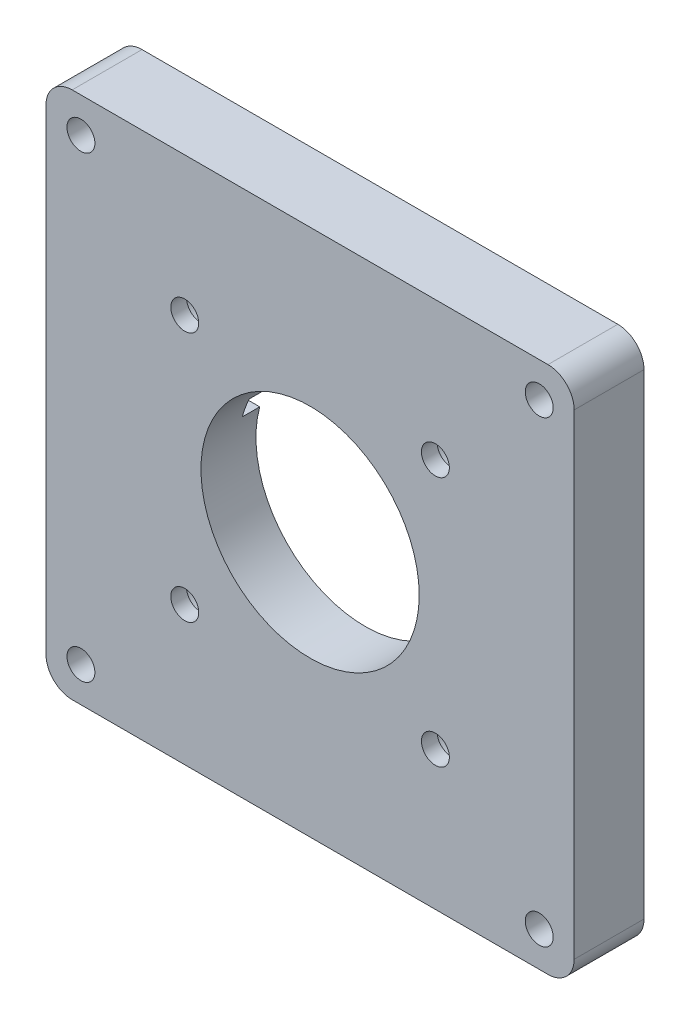
SolidWorks part; units mm, degrees
material "ABS"
ref_plane "Front Plane" through (0, 0, 0) normal (0, 0, 1) x (1, 0, 0)
ref_plane "Top Plane" through (0, 0, 0) normal (0, 1, 0) x (1, 0, 0)
ref_plane "Right Plane" through (0, 0, 0) normal (1, 0, 0) x (0, 0, -1)
sketch "ｽｹｯﾁ1" plane through (0, 0, 0) normal (0, 0, 1) x (1, 0, 0)
  line L0 (-19, 19) -> (-19, -19) construction
  line L1 (19.25, -19.25) -> (-19.25, -19.25)
  line L2 (19.25, -19.25) -> (19.25, 19.25)
  line L3 (19.25, 19.25) -> (-19.25, 19.25)
  line L4 (-19.25, -19.25) -> (-19.25, 19.25)
  line L5 (19.25, -19.25) -> (-19.25, 19.25) construction
  line L6 (19.25, 19.25) -> (-19.25, -19.25) construction
  line L7 (19, 19) -> (-19, 19) construction
  line L8 (30.25, 30.25) -> (-30.25, 30.25)
  line L9 (-30.25, -30.25) -> (-30.25, 30.25)
  line L10 (30.25, -30.25) -> (-30.25, -30.25)
  line L11 (30.25, -30.25) -> (30.25, 30.25)
  point P0 (0, 0)
  dimension "D1" = 0.25
  dimension "D2" = 0.25
  dimension "D3" = 11
extrude "ﾎﾞｽ - 押し出し1" add sketch "ｽｹｯﾁ1" along normal blind 8
sketch "ｽｹｯﾁ2" plane through (0, 0, 0) normal (0, 0, -1) x (-1, 0, 0)
  line L0 (-19.25, 20.75) -> (19.25, 20.75)
  line L1 (20.75, 19.25) -> (20.75, -19.25)
  line L2 (-19.25, 19.25) -> (19.25, 19.25) construction
  line L3 (-19.25, -19.25) -> (-19.25, 19.25) construction
  line L4 (19.25, -20.75) -> (-19.25, -20.75)
  line L5 (-20.75, -19.25) -> (-20.75, 19.25)
  line L6 (-19.25, 24.95) -> (19.25, 24.95)
  line L7 (24.95, 19.25) -> (24.95, -19.25)
  line L8 (19.25, -24.95) -> (-19.25, -24.95)
  line L9 (-24.95, -19.25) -> (-24.95, 19.25)
  arc A0 (19.25, 20.75) -> (20.75, 19.25) centre (19.25, 19.25) cw
  arc A1 (20.75, -19.25) -> (19.25, -20.75) centre (19.25, -19.25) cw
  arc A2 (-19.25, -20.75) -> (-20.75, -19.25) centre (-19.25, -19.25) cw
  arc A3 (-20.75, 19.25) -> (-19.25, 20.75) centre (-19.25, 19.25) cw
  arc A4 (19.25, 24.95) -> (24.95, 19.25) centre (19.25, 19.25) cw
  arc A5 (24.95, -19.25) -> (19.25, -24.95) centre (19.25, -19.25) cw
  arc A6 (-19.25, -24.95) -> (-24.95, -19.25) centre (-19.25, -19.25) cw
  arc A7 (-24.95, 19.25) -> (-19.25, 24.95) centre (-19.25, 19.25) cw
  point P24 (0, 0)
  dimension "D1" = 1.5
  dimension "D3" = 4.2
  dimension "D2" = 4
extrude "ｶｯﾄ - 押し出し1" cut sketch "ｽｹｯﾁ2" against normal blind 2.35
sketch "ｽｹｯﾁ3" plane through (0, 0, 0) normal (0, 0, -1) x (-1, 0, 0)
  line L4 (-30.25, 30.25) -> (30.25, 30.25) construction
  line L5 (30.25, 30.25) -> (30.25, -30.25) construction
  circle A0 centre (26.25, 26.25) radius 1.6
  circle A1 centre (26.25, -26.25) radius 1.6
  circle A2 centre (-26.25, -26.25) radius 1.6
  circle A3 centre (-26.25, 26.25) radius 1.6
  point P15 (0, 0)
  dimension "D1" = 3.2
  dimension "D2" = 4
  dimension "D3" = 4
  dimension "D4" = 4
extrude "ｶｯﾄ - 押し出し2" cut sketch "ｽｹｯﾁ3" against normal through all
ref_plane "平面1" through (0, 0, 1.2) normal (0, 0, 1) x (1, 0, 0)
sketch "ｽｹｯﾁ4" plane through (0, 0, 1.2) normal (0, 0, 1) x (1, 0, 0)
  line L0 (-19.25, -19.25) -> (19.25, -19.25) construction
  line L1 (19.25, -19.25) -> (19.25, 19.25) construction
  line L2 (-19.25, 19.25) -> (-19.25, -19.25) construction
  line L3 (19.25, 19.25) -> (-19.25, 19.25) construction
  line L4 (-19.25, -19.25) -> (19.25, -19.25)
  line L5 (19.25, -19.25) -> (19.25, 19.25)
  line L6 (-19.25, 19.25) -> (-19.25, -19.25)
  line L7 (19.25, 19.25) -> (-19.25, 19.25)
  circle A0 centre (0, 0) radius 12.5
  dimension "D1" = 25
extrude "ﾎﾞｽ - 押し出し2" add sketch "ｽｹｯﾁ4" along normal up to surface (6.8 mm away) up to face at (24.65, 26.25, 8)
hole_wizard "M3 すきま穴1" positions "ｽｹｯﾁ7" profile "ｽｹｯﾁ8" hole size "M3" standard "JIS" end condition through all
sketch "ｽｹｯﾁ7" plane through (0, 0, 1.2) normal (0, 0, -1) x (-1, 0, 0)
  point P0 (14.3543, 14.3543)
  point P3 (-14.3543, 14.3543)
  point P6 (-14.3543, -14.3543)
  point P9 (14.3543, -14.3543)
sketch "ｽｹｯﾁ8" plane through (-14.3543, 14.3543, 1.2) normal (1, 0, 0) x (0, 1, 0)
  line L0 (0, 0) -> (0, 6.8)
  line L1 (0, 6.8) -> (1.6, 6.8)
  line L2 (1.6, 6.8) -> (1.6, 0)
  line L5 (1.6, 0) -> (0, 0)
  line L11 (0, -6.35) -> (0, 107.95) construction
  dimension "通し穴の直径" = 3.2
  dimension "通し穴の深さ" = 6.8
sketch "ｽｹｯﾁ10" plane through (0, 0, 1.2) normal (0, 0, -1) x (-1, 0, 0)
  line L0 (16, 1) -> (16, 14.5) construction
  line L1 (-16, -16) -> (16, -16)
  line L2 (-16, -16) -> (-16, 16)
  line L3 (-16, 16) -> (16, 16)
  line L4 (16, -16) -> (16, 16)
  line L5 (-16, -16) -> (16, 16) construction
  line L6 (-16, 16) -> (16, -16) construction
  point P0 (0, 0)
extrude "ｶｯﾄ - 押し出し4" cut sketch "ｽｹｯﾁ10" against normal blind 0.5
sketch "ｽｹｯﾁ11" plane through (0, 0, 1.7) normal (0, 0, -1) x (-1, 0, 0)
  line L8 (11.25, 3.25) -> (15.75, 3.25)
  line L9 (11.25, 11.25) -> (11.25, 3.25)
  line L10 (15.75, 11.25) -> (11.25, 11.25)
  line L11 (15.75, 3.25) -> (15.75, 11.25)
  line L12 (11.25, 3.25) -> (15.75, 3.25)
  line L13 (11.25, 11.25) -> (11.25, 3.25)
  line L14 (15.75, 11.25) -> (11.25, 11.25)
  line L15 (15.75, 3.25) -> (15.75, 11.25)
  line L20 (-15.75, -7) -> (-15.75, -10.75)
  line L21 (-10.75, -7) -> (-15.75, -7)
  line L22 (-10.75, -10.75) -> (-10.75, -7)
  line L23 (-15.75, -10.75) -> (-10.75, -10.75)
  line L24 (-15.75, -7) -> (-15.75, -10.75)
  line L25 (-10.75, -7) -> (-15.75, -7)
  line L26 (-10.75, -10.75) -> (-10.75, -7)
  line L27 (-15.75, -10.75) -> (-10.75, -10.75)
  dimension "D1" = 0.25
  dimension "D2" = 0.25
extrude "ｶｯﾄ - 押し出し6" cut sketch "ｽｹｯﾁ11" against normal blind 2
sketch "ｽｹｯﾁ9" plane through (0, 0, 1.2) normal (0, 0, -1) x (-1, 0, 0)
  circle A2 centre (14.3543, 14.3543) radius 3
  circle A4 centre (-14.3543, 14.3543) radius 3
  circle A5 centre (14.3543, -14.3543) radius 3
  circle A6 centre (-14.3543, -14.3543) radius 3
  point P12 (0, 0)
  dimension "D1" = 6
  dimension "D2" = 4
extrude "ｶｯﾄ - 押し出し7" cut sketch "ｽｹｯﾁ9" against normal blind 5
fillet "ﾌｨﾚｯﾄ1" radius 3 4 edges at (-30.25, 30.25, 4) (30.25, 30.25, 4) (-30.25, -30.25, 4) (30.25, -30.25, 4)
equation "\"０・５\"=2"
